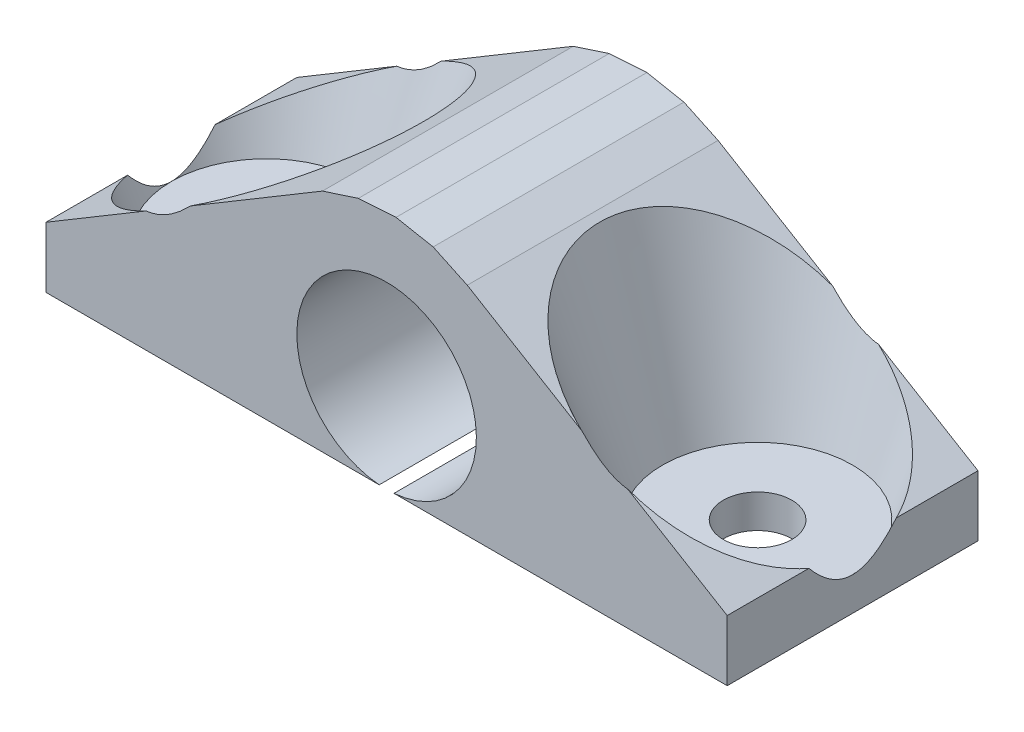
SolidWorks part; units mm, degrees
ref_plane "Front Plane" through (0, 0, 0) normal (0, 0, 1) x (1, 0, 0)
ref_plane "Top Plane" through (0, 0, 0) normal (0, 1, 0) x (1, 0, 0)
ref_plane "Right Plane" through (0, 0, 0) normal (1, 0, 0) x (0, 0, -1)
ref_plane "Plane1" through (0, 0, 8.25) normal (0, 0, 1) x (1, 0, 0)
sketch "Sketch1" plane through (0, 0, 8.25) normal (0, 0, 1) x (1, 0, 0)
  line L0 (22.4063, -1.9063) -> (5.308, 8.3641)
  line L1 (5.308, 8.3641) -> (3.0612, 9.4214)
  line L2 (3.0612, 9.4214) -> (0.622, 9.8867)
  line L3 (0.622, 9.8867) -> (-1.8563, 9.7308)
  line L4 (-1.8563, 9.7308) -> (-4.2179, 8.9634)
  line L5 (-4.2179, 8.9634) -> (-22.4062, -1.9063)
  line L6 (-22.4062, -1.9063) -> (-22.4062, -5.9062)
  line L7 (-22.4062, -5.9062) -> (22.4063, -5.9062)
  line L8 (22.4063, -5.9062) -> (22.4063, -1.9063)
extrude "Boss-Extrude1" add sketch "Sketch1" against normal blind 16.5
sketch "Sketch2" plane through (0, 0, 0) normal (0, 0, 1) x (1, 0, 0)
  line L0 (26.5314, 8.08) -> (16.1562, 8.08)
  line L1 (16.1562, 8.08) -> (16.1562, -5.9062)
  line L2 (16.1562, -5.9062) -> (18.4062, -5.9062)
  line L3 (18.4062, -5.9062) -> (18.4062, -3.7063)
  line L4 (18.4062, -3.7063) -> (22.4062, -3.7063)
  line L5 (22.4062, -3.7063) -> (26.5314, 8.08)
  line L6 (16.1562, 8.08) -> (16.1562, -5.9062) construction
revolve "Cut-Revolve1" cut sketch "Sketch2" angle 360 about L6
ref_plane "Plane2" through (0, 0, 0) normal (0, 0, -1) x (-1, 0, 0)
sketch "Sketch3" plane through (0, 0, 0) normal (0, 0, -1) x (-1, 0, 0)
  line L0 (13.9062, -5.9063) -> (16.1562, -5.9063)
  line L1 (16.1562, -5.9063) -> (16.1562, 8.0159)
  line L2 (16.1562, 8.0159) -> (5.8035, 8.0159)
  line L3 (5.8035, 8.0159) -> (9.9062, -3.7063)
  line L4 (9.9062, -3.7063) -> (13.9062, -3.7063)
  line L5 (13.9062, -3.7063) -> (13.9062, -5.9063)
  line L6 (16.1562, -5.9063) -> (16.1562, 8.0159) construction
revolve "Cut-Revolve2" cut sketch "Sketch3" angle 360 about L6
hole_wizard "M10 Clearance Hole1" positions "Sketch5" profile "Sketch4" hole size "M10" standard "ANSI Metric"
sketch "Sketch5" plane through (0, 0, 8.25) normal (0, 0, 1) x (1, 0, 0)
  point P0 (0, -0.02)
sketch "Sketch4" plane through (0, -0.02, 8.25) normal (1, 0, 0) x (0, -1, 0)
  line L0 (0, 0) -> (0, 16.5)
  line L1 (0, 16.5) -> (5.9062, 16.5)
  line L2 (5.9062, 16.5) -> (5.9062, 0)
  line L5 (5.9062, 0) -> (0, 0)
  line L11 (0, -6.35) -> (0, 107.95) construction
  dimension "Thru Hole Dia." = 11.8125
  dimension "Thru Hole Depth" = 16.5
